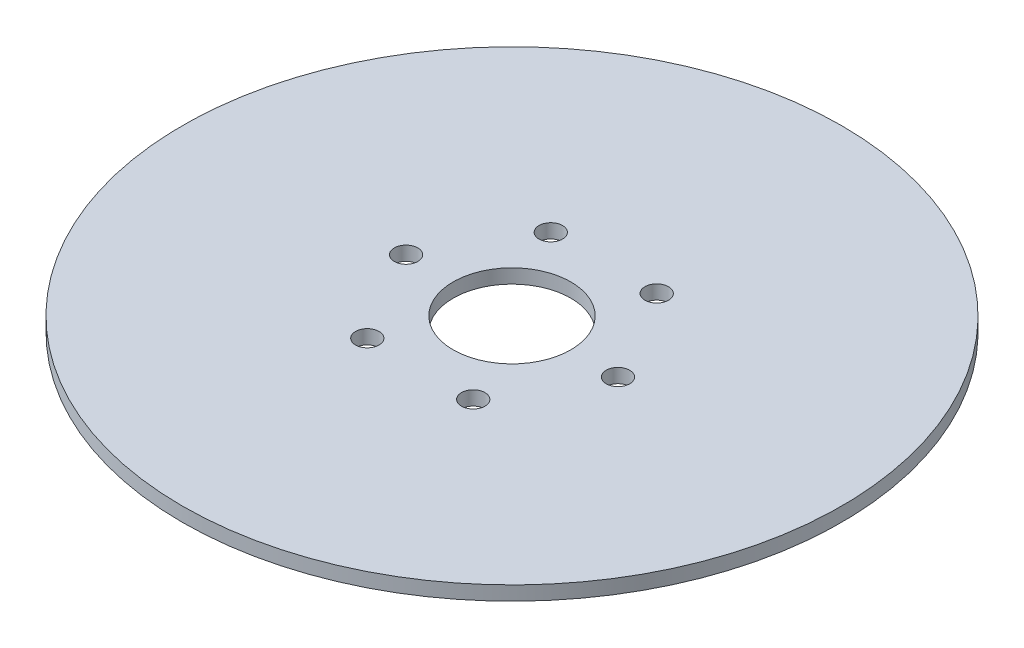
SolidWorks part; units mm, degrees
material "ABS"
ref_plane "前视基准面" through (0, 0, 0) normal (0, 0, 1) x (1, 0, 0)
ref_plane "上视基准面" through (0, 0, 0) normal (0, 1, 0) x (1, 0, 0)
ref_plane "右视基准面" through (0, 0, 0) normal (1, 0, 0) x (0, 0, -1)
sketch "草图1" plane through (0, 0, 0) normal (0, 1, 0) x (1, 0, 0)
  circle A0 centre (0, 0) radius 70
  circle A1 centre (0, 0) radius 12.5
  circle A2 centre (0, 0) radius 22.5 construction
  circle A3 centre (22.5, 0) radius 2.5
  circle A4 centre (11.25, -19.4856) radius 2.5
  circle A5 centre (-11.25, -19.4856) radius 2.5
  circle A6 centre (-22.5, 0) radius 2.5
  circle A7 centre (-11.25, 19.4856) radius 2.5
  circle A8 centre (11.25, 19.4856) radius 2.5
  point P20 (0, 0)
  dimension "D1" = 140
  dimension "D2" = 25
  dimension "D3" = 45
  dimension "D4" = 5
  dimension "D5" = 6
extrude "凸台-拉伸1" add sketch "草图1" along normal blind 3
